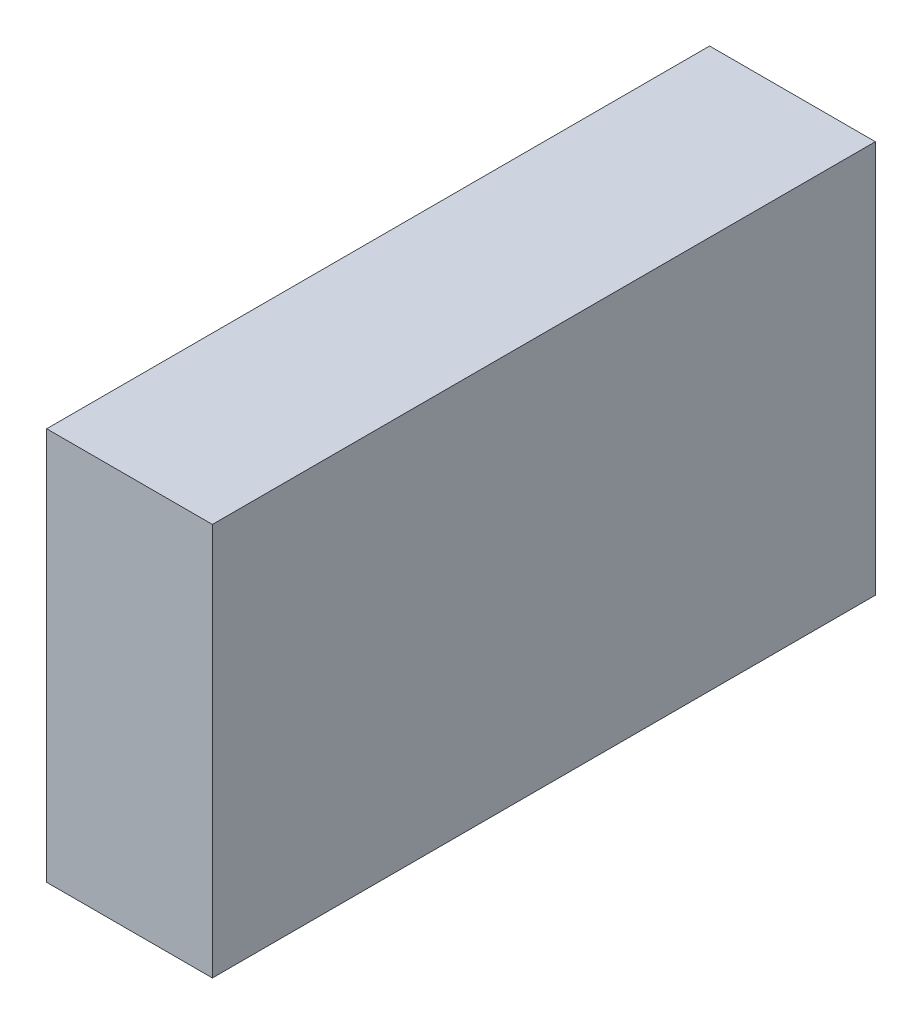
SolidWorks part; units mm, degrees
ref_plane "Front Plane" through (0, 0, 0) normal (0, 0, 1) x (1, 0, 0)
ref_plane "Top Plane" through (0, 0, 0) normal (0, 1, 0) x (1, 0, 0)
ref_plane "Right Plane" through (0, 0, 0) normal (1, 0, 0) x (0, 0, -1)
sketch "Sketch1" plane through (0, 0, 0) normal (1, 0, 0) x (0, 0, -1)
  line L1 (0, 0) -> (40, 0)
  line L2 (0, 0) -> (0, 23.7)
  line L3 (0, 23.7) -> (40, 23.7)
  line L4 (40, 0) -> (40, 23.7)
extrude "Boss-Extrude1" add sketch "Sketch1" along normal blind 10
